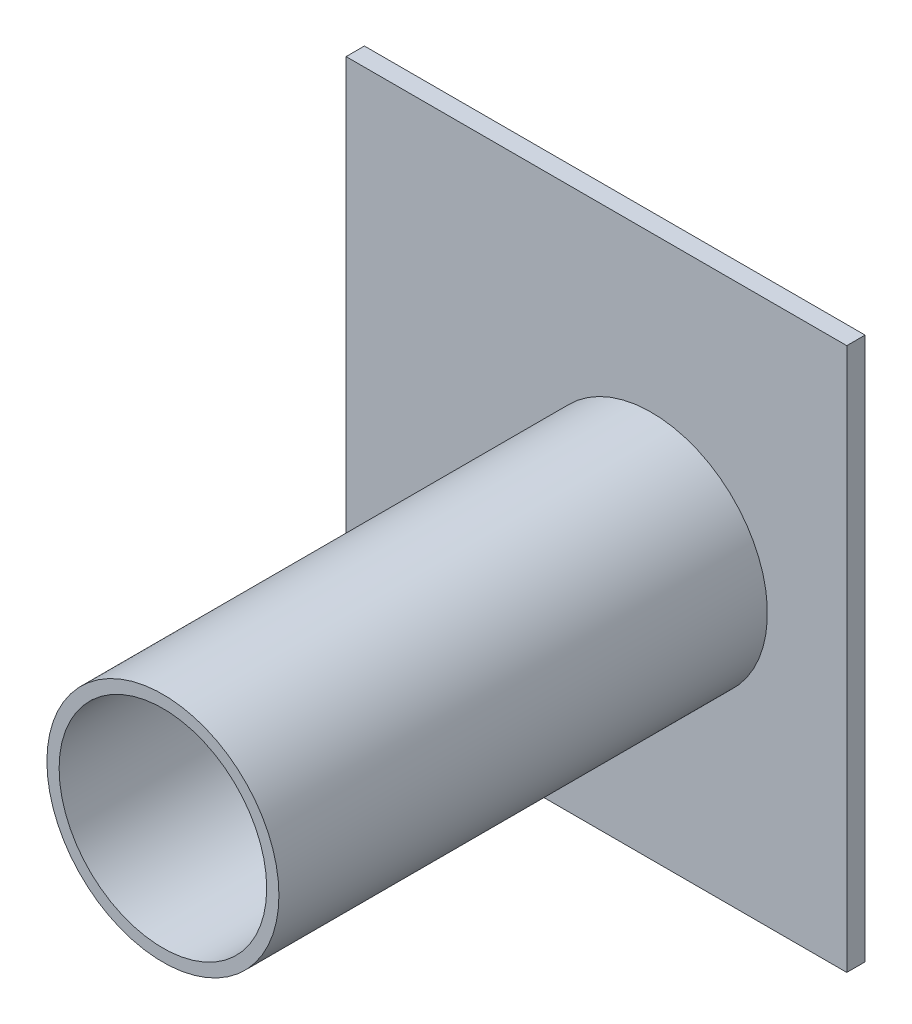
SolidWorks part; units mm, degrees
material "Nylon 101"
ref_plane "Front Plane" through (0, 0, 0) normal (0, 0, 1) x (1, 0, 0)
ref_plane "Top Plane" through (0, 0, 0) normal (0, 1, 0) x (1, 0, 0)
ref_plane "Right Plane" through (0, 0, 0) normal (1, 0, 0) x (0, 0, -1)
sketch "Base" plane through (0, 0, 0) normal (0, 0, 1) x (1, 0, 0)
  line L0 (-50, -44.45) -> (0, -44.45)
  line L2 (-50, -44.45) -> (-50, 44.45)
  line L3 (-50, 44.45) -> (32, 44.45)
  line L5 (0, 44.45) -> (0, -44.45) construction
  line L6 (-50, 0) -> (32, 0) construction
  line L7 (32, 44.45) -> (32, -44.45)
  line L8 (0, -44.45) -> (32, -44.45)
  circle A0 centre (0, 0) radius 17
  circle A1 centre (0, 0) radius 19 construction
  point P0 (0, 0)
  dimension "D1" = 88.9
  dimension "D3" = 34
  dimension "D4" = 38
  dimension "D2" = 50
  dimension "D5" = 32
extrude "Boss-Extrude1" add sketch "Base" along normal blind 3 contours L2 L3 L7 L8 L0
sketch "Sketch1" plane through (0, 0, 3) normal (0, 0, 1) x (1, 0, 0)
  circle A0 centre (0, 0) radius 17 construction
  circle A1 centre (0, 0) radius 17
  circle A2 centre (0, 0) radius 19 construction
  circle A3 centre (0, 0) radius 19
extrude "Boss-Extrude2" add sketch "Sketch1" along normal blind 80
